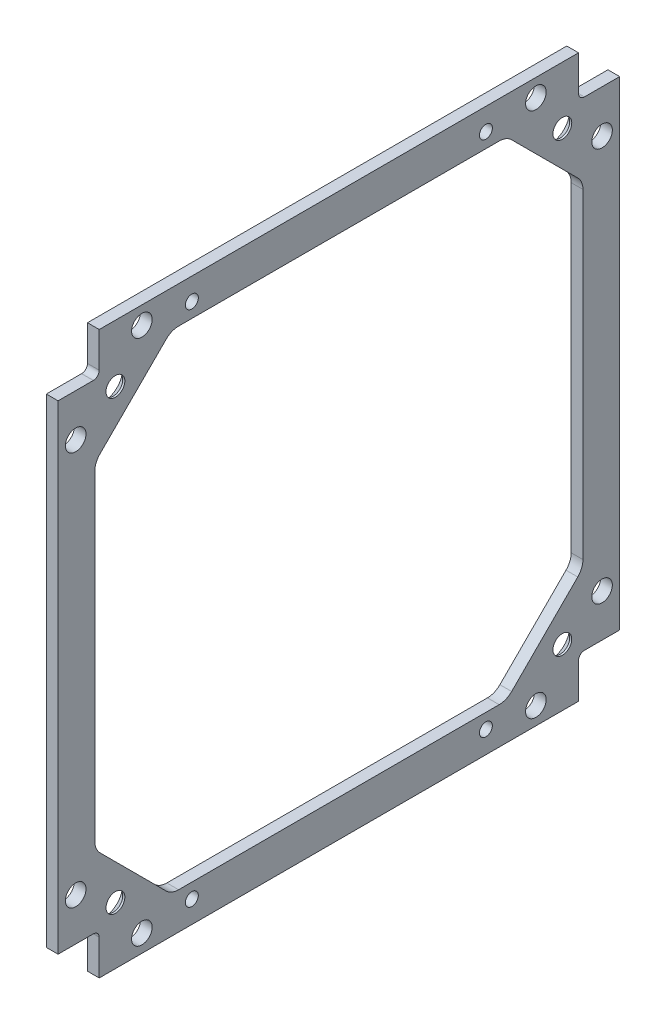
SolidWorks part; units mm, degrees
ref_plane "Front Plane" through (0, 0, 0) normal (0, 0, 1) x (1, 0, 0)
ref_plane "Top Plane" through (0, 0, 0) normal (0, 1, 0) x (1, 0, 0)
ref_plane "Right Plane" through (0, 0, 0) normal (1, 0, 0) x (0, 0, -1)
sketch "Sketch2" plane through (-51.4936, 0, 0) normal (-1, 0, 0) x (0, 0, 1)
  line L0 (0.4347, 3.9519) -> (7.4347, 3.9519)
  line L1 (7.4347, 3.9519) -> (7.4347, 85.4519)
  line L2 (0.4347, 92.4519) -> (-81.0653, 92.4519)
  line L3 (-88.0653, 85.4519) -> (-88.0653, 3.9519)
  line L4 (-81.0653, -3.0481) -> (0.4347, -3.0481)
  line L5 (0.4347, -3.0481) -> (0.4347, 3.9519)
  line L6 (-81.0653, -3.0481) -> (-81.0653, 3.9519)
  line L7 (-81.0653, 3.9519) -> (-88.0653, 3.9519)
  line L8 (-88.0653, 44.7019) -> (7.4347, 44.7019) construction
  line L9 (-81.8153, 73.2019) -> (-81.8153, 16.2019)
  line L10 (-40.3153, 92.4519) -> (-40.3153, -3.0481) construction
  line L11 (-88.0653, 85.4519) -> (-81.0653, 85.4519)
  line L12 (-81.0653, 92.4519) -> (-81.0653, 85.4519)
  line L13 (-68.8153, 3.2019) -> (-11.8153, 3.2019)
  line L14 (-81.8153, 73.2019) -> (-68.8153, 86.2019)
  line L15 (7.4347, 85.4519) -> (0.4347, 85.4519)
  line L16 (0.4347, 92.4519) -> (0.4347, 85.4519)
  line L17 (1.1847, 16.2019) -> (1.1847, 73.2019)
  line L18 (-11.8153, 86.2019) -> (1.1847, 73.2019)
  line L19 (-11.8153, 86.2019) -> (-68.8153, 86.2019)
  line L28 (-11.8153, 3.2019) -> (1.1847, 16.2019)
  line L29 (-81.8153, 16.2019) -> (-68.8153, 3.2019)
  dimension "D1" = 7
  dimension "D2" = 28.5
  dimension "D3" = 95.5
  dimension "D4" = 95.5
  dimension "D5" = 41.5
  dimension "D6" = 41.5
  dimension "D7" = 28.5
  dimension "D8" = 41.5
  dimension "D9" = 41.5
extrude "Boss-Extrude2" add sketch "Sketch2" along normal blind 2
hole_wizard "Ø3.5 (3.5) Diameter Hole1" positions "Sketch19" profile "Sketch18" hole size "Ø3.5" standard "Ansi Metric" end condition up to next
sketch "Sketch19" plane through (-53.4936, 0, 0) normal (-1, 0, 0) x (0, 0, 1)
  line L1 (-81.0653, -3.0481) -> (0.4347, -3.0481) construction
  line L2 (-88.0653, 85.4519) -> (-88.0653, 3.9519) construction
  line L7 (7.4347, 3.9519) -> (7.4347, 85.4519) construction
  line L10 (0.4347, 92.4519) -> (-81.0653, 92.4519) construction
  line L13 (-88.0653, 44.7019) -> (7.4347, 44.7019) construction
  line L15 (-40.3153, 92.4519) -> (-40.3153, -3.0481) construction
  point P0 (-73.8153, -0.0481)
  point P6 (-85.0653, 11.2019)
  point P8 (-85.0653, 78.2019)
  point P10 (-73.8153, 89.4519)
  point P12 (-6.8153, 89.4519)
  point P14 (4.4347, 78.2019)
  point P16 (4.4347, 11.2019)
  point P18 (-6.8153, -0.0481)
  dimension "D1" = 44.75
  dimension "D2" = 33.5
  dimension "D3" = 33.5
  dimension "D4" = 44.75
  dimension "D5" = 33.5
  dimension "D6" = 44.75
  dimension "D7" = 33.5
  dimension "D8" = 44.75
sketch "Sketch18" plane through (-53.4936, -0.0481, -73.8153) normal (0, 1, 0) x (0, 0, 1)
  line L0 (0, 0) -> (0, 2)
  line L1 (0, 2) -> (1.75, 2)
  line L2 (1.75, 2) -> (1.75, 0)
  line L5 (1.75, 0) -> (0, 0)
  line L11 (0, -6.35) -> (0, 107.95) construction
  dimension "Thru Hole Dia." = 3.5
  dimension "Thru Hole Depth" = 2
hole_wizard "CSK for M3 Flat Countersunk Head Screw5" positions "3DSketch2" profile "Sketch24" countersink size "M3" standard "JIS" end condition up to next
sketch3d "3DSketch2"
  line L8 (-53.4936, 44.7019, -88.0653) -> (-53.4936, 44.7019, 7.4347) construction
  line L9 (-53.4936, 85.4519, -88.0653) -> (-53.4936, 3.9519, -88.0653) construction
  line L10 (-53.4936, 3.9519, 7.4347) -> (-53.4936, 85.4519, 7.4347) construction
  line L12 (-53.4936, 92.4519, -40.3153) -> (-53.4936, -3.0481, -40.3153) construction
  line L13 (-53.4936, 92.4519, 0.4347) -> (-53.4936, 92.4519, -81.0653) construction
  line L14 (-53.4936, -3.0481, -81.0653) -> (-53.4936, -3.0481, 0.4347) construction
  point P0 (-53.4936, 6.7019, -78.3153)
  point P2 (-53.4936, 82.7019, -78.3153)
  point P4 (-53.4936, 82.7019, -2.3153)
  point P19 (-53.4936, 6.7019, -2.3153)
  dimension "D1" = 38
  dimension "D2" = 38
  dimension "D3" = 38
  dimension "D4" = 38
  dimension "D5" = 38
  dimension "D6" = 38
  dimension "D7" = 38
  dimension "D8" = 38
sketch "Sketch24" plane through (-53.4936, 6.7019, -78.3153) normal (0, 1, 0) x (0, 0, 1)
  line L0 (0, 0) -> (0, 2)
  line L1 (0, 2) -> (1.6, 2)
  line L2 (1.6, 2) -> (1.6, 1.65)
  line L3 (1.6, 1.65) -> (3.25, 0)
  line L5 (3.25, 0) -> (0, 0)
  line L6 (-1.6, 1.65) -> (-3.25, 0) construction
  line L11 (0, -6.35) -> (0, 107.95) construction
  dimension "Thru Hole Dia." = 3.2
  dimension "Thru Hole Depth" = 2
  dimension "Near C'Sink Dia." = 6.5
  dimension "Near C'Sink Angle" = 90
hole_wizard "Ø2.2 (2.2) Diameter Hole1" positions "3DSketch3" profile "Sketch25" hole size "Ø2.2" standard "Ansi Metric" end condition up to next
sketch3d "3DSketch3"
  line L0 (-53.4936, 92.4519, 0.4347) -> (-53.4936, 92.4519, -81.0653) construction
  line L3 (-53.4936, 3.9519, 7.4347) -> (-53.4936, 85.4519, 7.4347) construction
  line L4 (-53.4936, -3.0481, -81.0653) -> (-53.4936, -3.0481, 0.4347) construction
  line L6 (-53.4936, 85.4519, -88.0653) -> (-53.4936, 3.9519, -88.0653) construction
  line L7 (-53.4936, 44.7019, -88.0653) -> (-53.4936, 44.7019, 7.4347) construction
  line L9 (-53.4936, 92.4519, -40.3153) -> (-53.4936, -3.0481, -40.3153) construction
  point P0 (-53.4936, 88.7019, -65.3153)
  point P2 (-53.4936, 88.7019, -15.3153)
  point P4 (-53.4936, 0.7019, -65.3153)
  point P6 (-53.4936, 0.7019, -15.3153)
  dimension "D1" = 44
  dimension "D2" = 25
  dimension "D3" = 25
  dimension "D4" = 44
  dimension "D5" = 44
  dimension "D6" = 25
  dimension "D7" = 25
  dimension "D8" = 44
sketch "Sketch25" plane through (-53.4936, 88.7019, -65.3153) normal (0, 1, 0) x (0, 0, 1)
  line L0 (0, 0) -> (0, 2)
  line L1 (0, 2) -> (1.1, 2)
  line L2 (1.1, 2) -> (1.1, 0)
  line L5 (1.1, 0) -> (0, 0)
  line L11 (0, -6.35) -> (0, 107.95) construction
  dimension "Thru Hole Dia." = 2.2
  dimension "Thru Hole Depth" = 2
fillet "Fillet1" radius 3 8 edges at (-52.4936, 16.2019, 1.1847) (-52.4936, 3.2019, -11.8153) (-52.4936, 3.2019, -68.8153) (-52.4936, 16.2019, -81.8153) (-52.4936, 73.2019, 1.1847) (-52.4936, 86.2019, -11.8153) (-52.4936, 73.2019, -81.8153) (-52.4936, 86.2019, -68.8153)
fillet "Fillet2" radius 1 4 edges at (-52.4936, 85.4519, -81.0653) (-52.4936, 85.4519, 0.4347) (-52.4936, 3.9519, 0.4347) (-52.4936, 3.9519, -81.0653)
